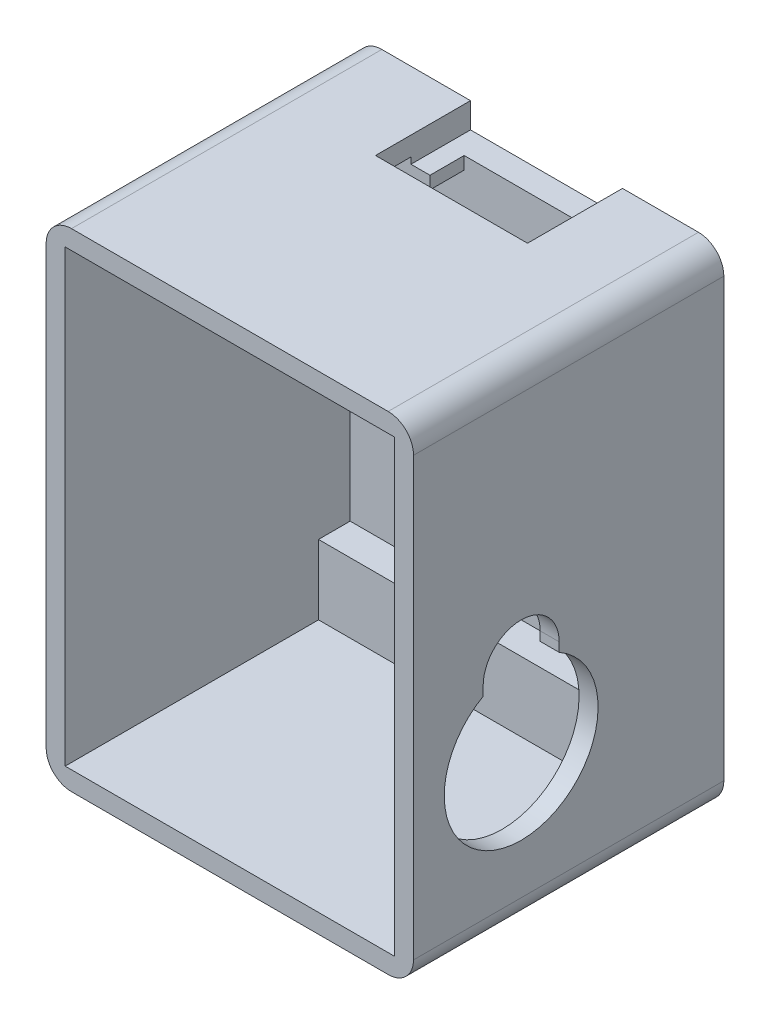
SolidWorks part; units mm, degrees
ref_plane "前视基准面" through (0, 0, 0) normal (0, 0, 1) x (1, 0, 0)
ref_plane "上视基准面" through (0, 0, 0) normal (0, 1, 0) x (1, 0, 0)
ref_plane "右视基准面" through (0, 0, 0) normal (1, 0, 0) x (0, 0, -1)
sketch "草图1" plane through (0, 0, 0) normal (0, 0, 1) x (1, 0, 0)
  line L1 (0, 0) -> (29, 0)
  line L2 (0, 0) -> (0, -38.5)
  line L3 (0, -38.5) -> (29, -38.5)
  line L4 (29, 0) -> (29, -38.5)
extrude "凸台-拉伸1" add sketch "草图1" along normal blind 24
shell "抽壳1" thickness 1.5
sketch "草图2" plane through (0, 0, 0) normal (0, 0, -1) x (-1, 0, 0)
  line L0 (-29, 0) -> (0, 0) construction
  line L1 (-21, 0) -> (-9, 0)
  line L2 (-21, 0) -> (-21, -2)
  line L3 (-21, -2) -> (-9, -2)
  line L4 (-9, 0) -> (-9, -2)
  line L5 (-29, -38.5) -> (-29, 0) construction
  line L6 (0, 0) -> (0, -38.5) construction
  dimension "D1" = 8
  dimension "D2" = 9
sketch "草图5" plane through (27.5, 0, 0) normal (-1, 0, 0) x (0, 0, 1)
  line L0 (24, -1.5) -> (1.5, -1.5) construction
  line L1 (4.2, -1.5) -> (1.5, -1.5)
  line L2 (4.2, -1.5) -> (4.2, -3)
  line L3 (4.2, -3) -> (1.5, -3)
  line L4 (1.5, -1.5) -> (1.5, -3)
  line L5 (1.5, -37) -> (1.5, -1.5) construction
sketch "草图6" plane through (1.5, 0, 0) normal (1, 0, 0) x (0, 0, -1)
  line L0 (-24, -1.5) -> (-1.5, -1.5) construction
  line L1 (-4.2, -1.5) -> (-1.5, -1.5)
  line L2 (-4.2, -1.5) -> (-4.2, -3)
  line L3 (-4.2, -3) -> (-1.5, -3)
  line L4 (-1.5, -1.5) -> (-1.5, -3)
  line L5 (-1.5, -1.5) -> (-1.5, -37) construction
sketch "草图7" plane through (0, 0, 1.5) normal (0, 0, 1) x (1, 0, 0)
  line L0 (27.5, -37) -> (27.5, -1.5) construction
  line L1 (27.5, -31.5) -> (1.5, -31.5)
  line L2 (27.5, -31.5) -> (27.5, -37)
  line L3 (27.5, -37) -> (1.5, -37)
  line L4 (1.5, -31.5) -> (1.5, -37)
  line L5 (1.5, -37) -> (27.5, -37) construction
extrude "凸台-拉伸7" add sketch "草图7" along normal blind 2.5
extrude "凸台-拉伸8" add sketch "草图5" along normal blind 8
extrude "凸台-拉伸9" add sketch "草图6" along normal blind 9
sketch "草图9" plane through (0, 0, 0) normal (0, 0, -1) x (-1, 0, 0)
  line L1 (0, 0) -> (-29, 0)
  line L2 (0, 0) -> (0, -38.5)
  line L3 (0, -38.5) -> (-29, -38.5)
  line L4 (-29, 0) -> (-29, -38.5)
extrude "凸台-拉伸10" add sketch "草图9" along normal blind 0.5
fillet "圆角3" radius 2 4 edges at (29, 0, 11.75) (29, -38.5, 11.75) (0, -38.5, 11.75) (0, 0, 11.75)
extrude "切除-拉伸8" cut sketch "草图2" against normal blind 7 and the other way blind 1.5
sketch "草图10" plane through (29, 0, 0) normal (1, 0, 0) x (0, 0, -1)
  line L0 (-24, -36.5) -> (0.5, -36.5) construction
  line L1 (0.5, -2) -> (0.5, -36.5) construction
  line L2 (-18.5, -20.5) -> (-18.5, -21.2207)
  line L3 (-12.5, -20.5) -> (-12.5, -21.2207)
  circle A0 centre (-15.5, -26.5) radius 6.0721
  circle A1 centre (-15.5, -20.5) radius 3
  dimension "D3" = 6
  dimension "D1" = 10
  dimension "D2" = 16
extrude "切除-拉伸9" cut sketch "草图10" against normal blind 1.5 contours A1 A0 | A1 A0 | A1 L2 A0 | A0 A1 | A1 A0 L3
